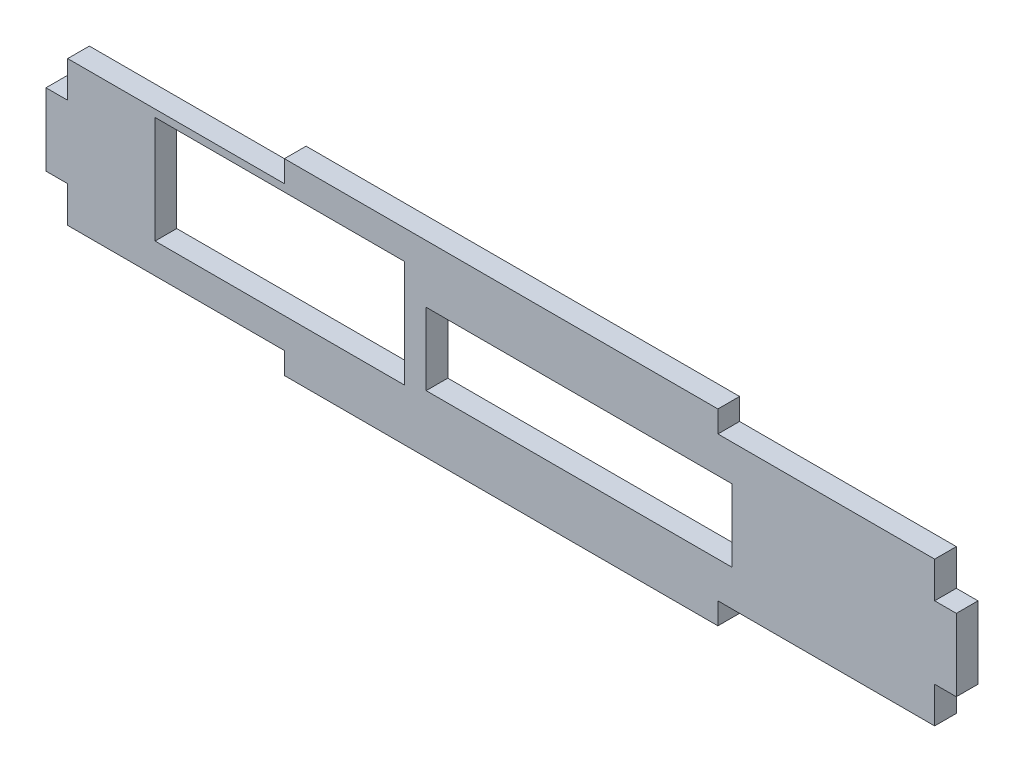
SolidWorks part; units mm, degrees
ref_plane "Front Plane" through (0, 0, 0) normal (0, 0, 1) x (1, 0, 0)
ref_plane "Top Plane" through (0, 0, 0) normal (0, 1, 0) x (1, 0, 0)
ref_plane "Right Plane" through (0, 0, 0) normal (1, 0, 0) x (0, 0, -1)
sketch "Sketch1" plane through (0, 0, 0) normal (0, 0, 1) x (1, 0, 0)
  line L0 (0, 10) -> (-1.5, 10) construction
  line L1 (0, 0) -> (120, 0) construction
  line L2 (0, 0) -> (0, 20) construction
  line L3 (0, 20) -> (120, 20) construction
  line L4 (120, 0) -> (120, 20) construction
  line L5 (60, 20) -> (60, 21.5) construction
  line L6 (60, 0) -> (60, -1.5) construction
  line L7 (120, 10) -> (121.5, 10) construction
  line L8 (0, 0) -> (0, 5)
  line L9 (-3, 15) -> (0, 15) construction
  line L10 (-3, 15) -> (-3, 5) construction
  line L11 (-3, 5) -> (0, 5) construction
  line L12 (0, 15) -> (0, 5) construction
  line L13 (-3, 15) -> (0, 5) construction
  line L14 (-3, 5) -> (0, 15) construction
  line L15 (30, 23) -> (90, 23) construction
  line L16 (30, 23) -> (30, 20) construction
  line L17 (30, 20) -> (90, 20) construction
  line L18 (90, 23) -> (90, 20) construction
  line L19 (30, 23) -> (90, 20) construction
  line L20 (30, 20) -> (90, 23) construction
  line L21 (123, 15) -> (120, 15) construction
  line L22 (123, 15) -> (123, 5) construction
  line L23 (123, 5) -> (120, 5) construction
  line L24 (120, 15) -> (120, 5) construction
  line L25 (123, 15) -> (120, 5) construction
  line L26 (123, 5) -> (120, 15) construction
  line L27 (30, -3) -> (90, -3) construction
  line L28 (30, -3) -> (30, 0) construction
  line L29 (30, 0) -> (90, 0) construction
  line L30 (90, -3) -> (90, 0) construction
  line L31 (30, -3) -> (90, 0) construction
  line L32 (30, 0) -> (90, -3) construction
  line L33 (0, 5) -> (-3, 5)
  line L34 (-3, 5) -> (-3, 15)
  line L35 (-3, 15) -> (0, 15)
  line L36 (0, 15) -> (0, 20)
  line L37 (0, 20) -> (30, 20)
  line L38 (30, 20) -> (30, 23)
  line L39 (30, 23) -> (90, 23)
  line L40 (90, 23) -> (90, 20)
  line L41 (90, 20) -> (120, 20)
  line L42 (120, 20) -> (120, 15)
  line L43 (120, 15) -> (123, 15)
  line L44 (123, 15) -> (123, 5)
  line L45 (123, 5) -> (120, 5)
  line L46 (120, 5) -> (120, 0)
  line L47 (120, 0) -> (90, 0)
  line L48 (90, 0) -> (90, -3)
  line L49 (90, -3) -> (30, -3)
  line L50 (30, -3) -> (30, 0)
  line L51 (30, 0) -> (0, 0)
  line L53 (12.0944, 18.9905) -> (46.6343, 18.9905)
  line L54 (12.0944, 18.9905) -> (12.0944, 4.171)
  line L55 (12.0944, 4.171) -> (46.6343, 4.171)
  line L56 (46.6343, 18.9905) -> (46.6343, 4.171)
  line L57 (49.6156, 15) -> (91.9431, 15)
  line L58 (49.6156, 15) -> (49.6156, 5)
  line L59 (49.6156, 5) -> (91.9431, 5)
  line L60 (91.9431, 15) -> (91.9431, 5)
extrude "Boss-Extrude1" add sketch "Sketch1" along normal blind 3
